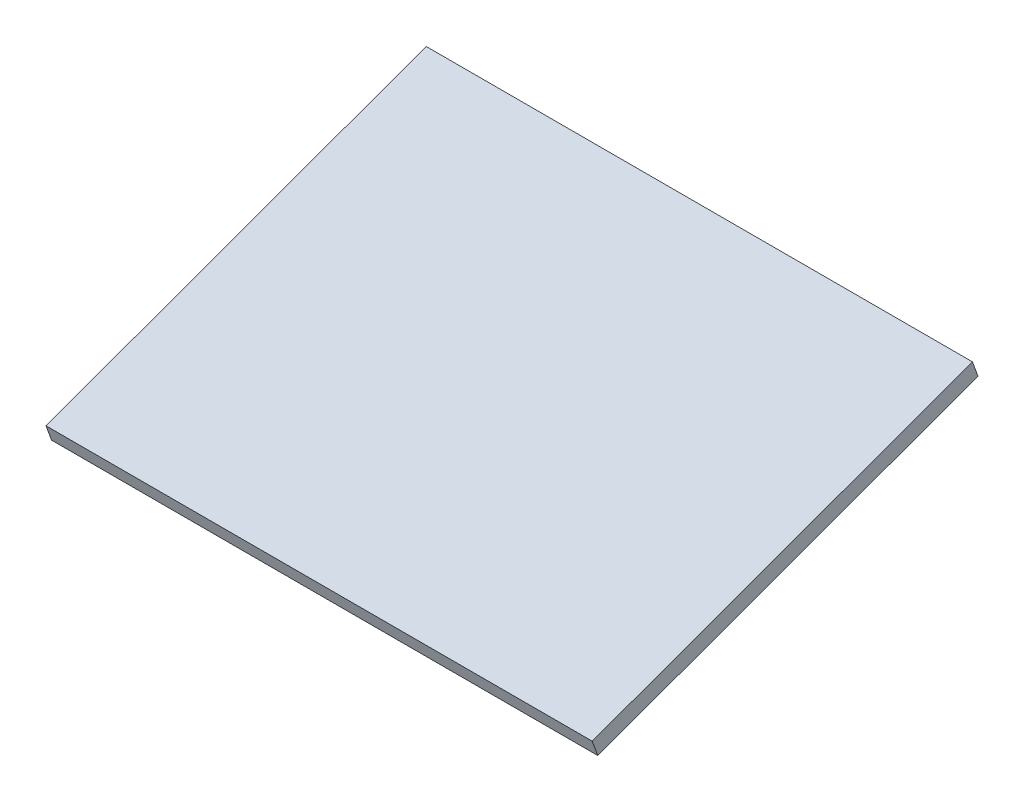
SolidWorks part; units mm, degrees
ref_plane "Front Plane" through (0, 0, 0) normal (0, 0, 1) x (1, 0, 0)
ref_plane "Top Plane" through (0, 0, 0) normal (0, 1, 0) x (1, 0, 0)
ref_plane "Right Plane" through (0, 0, 0) normal (1, 0, 0) x (0, 0, -1)
ref_plane "Plane1" through (-27, 0, 0) normal (1, 0, 0) x (0, 0, -1)
sketch "Sketch1" plane through (-27, 0, 0) normal (1, 0, 0) x (0, 0, -1)
  line L0 (10.3015, 232.7899) -> (-27.2862, 219.1091)
  line L1 (-27.2862, 219.1091) -> (-27.8334, 220.6126)
  line L2 (-27.8334, 220.6126) -> (9.7543, 234.2934)
  line L3 (9.7543, 234.2934) -> (10.3015, 232.7899)
extrude "Boss-Extrude1" add sketch "Sketch1" along normal blind 54
